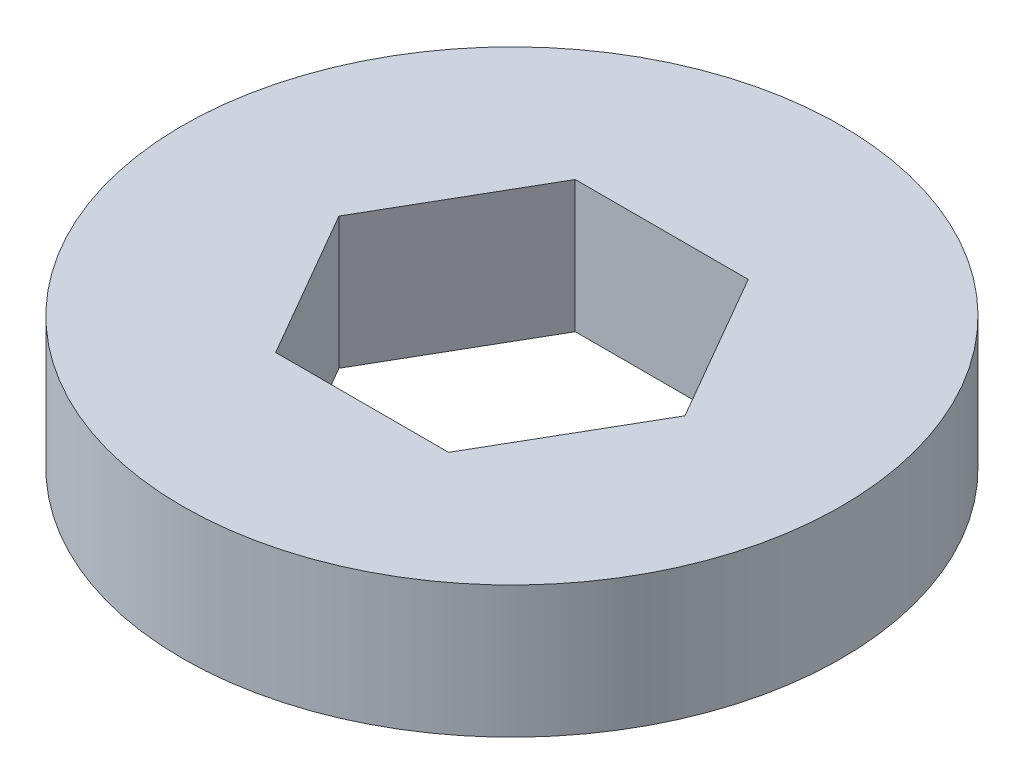
SolidWorks part; units mm, degrees
ref_plane "Front Plane" through (0, 0, 0) normal (0, 0, 1) x (1, 0, 0)
ref_plane "Top Plane" through (0, 0, 0) normal (0, 1, 0) x (1, 0, 0)
ref_plane "Right Plane" through (0, 0, 0) normal (1, 0, 0) x (0, 0, -1)
sketch "Sketch1" plane through (0, 0, 0) normal (0, 1, 0) x (1, 0, 0)
  line L1 (7.3323, 0) -> (3.6662, 6.35)
  line L2 (3.6662, 6.35) -> (-3.6662, 6.35)
  line L3 (-3.6662, 6.35) -> (-7.3323, 0)
  line L4 (-7.3323, 0) -> (-3.6662, -6.35)
  line L5 (-3.6662, -6.35) -> (3.6662, -6.35)
  line L6 (3.6662, -6.35) -> (7.3323, 0)
  circle A0 centre (0, 0) radius 13.97
  circle A1 centre (0, 0) radius 6.35 construction
  dimension "D1" = 27.94
  dimension "D2" = 12.7
extrude "Boss-Extrude1" add sketch "Sketch1" along normal blind 5.588
